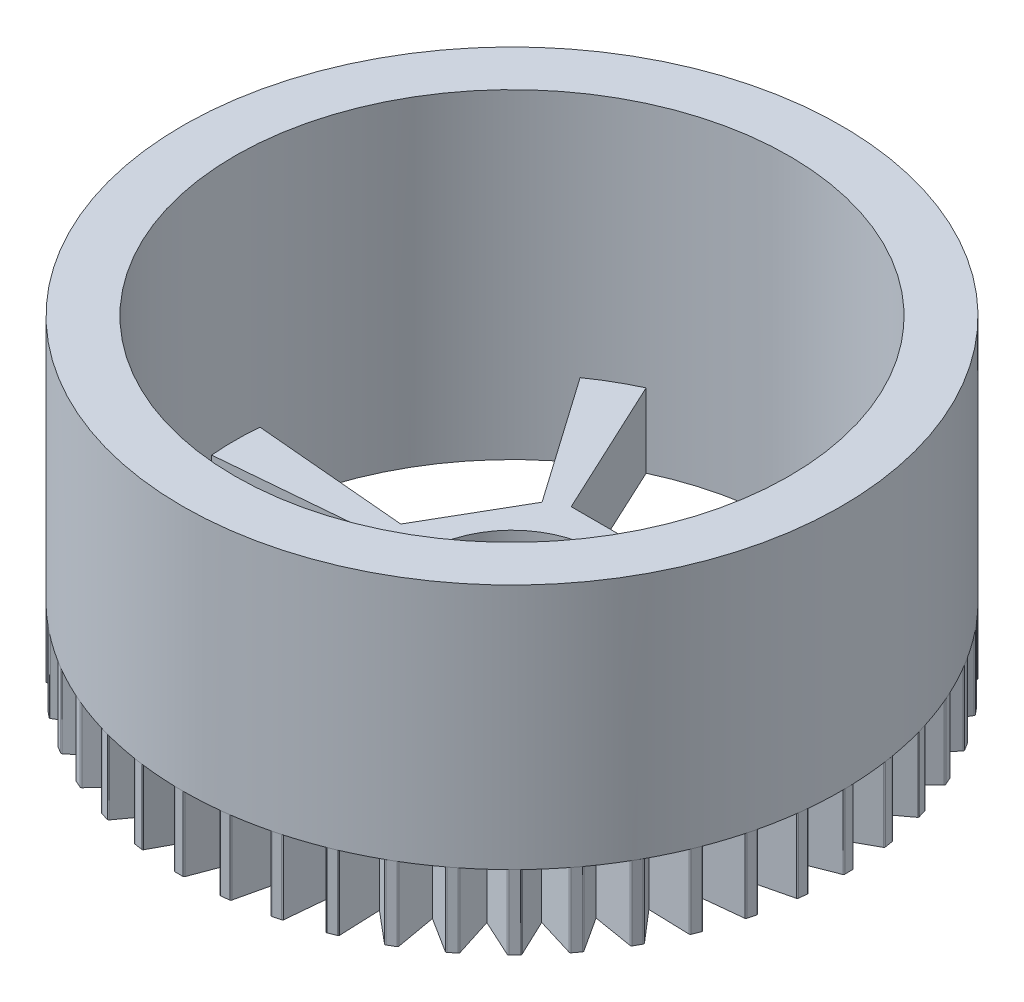
SolidWorks part; units mm, degrees
ref_plane "前视基准面" through (0, 0, 0) normal (0, 0, 1) x (1, 0, 0)
ref_plane "上视基准面" through (0, 0, 0) normal (0, 1, 0) x (1, 0, 0)
ref_plane "右视基准面" through (0, 0, 0) normal (1, 0, 0) x (0, 0, -1)
other "Configuration Table"
sketch "草图2" plane through (0, 0, 0) normal (0, 1, 0) x (1, 0, 0)
  line L0 (-2.5981, 4.5) -> (2.5981, 4.5)
  line L1 (0, 0) -> (2.5981, 4.5) construction
  line L2 (-2.5981, 4.5) -> (0, 0) construction
  line L3 (2.5981, 4.5) -> (5.1962, 0)
  line L4 (5.1962, 0) -> (2.5981, -4.5)
  line L5 (2.5981, -4.5) -> (-2.5981, -4.5)
  line L6 (-2.5981, -4.5) -> (-5.1962, 0)
  line L7 (-5.1962, 0) -> (-2.5981, 4.5)
  line L8 (2.5981, -4.5) -> (5.625, -9.7428) construction
  line L9 (2.8479, -4.0673) -> (6.4527, -9.2155)
  line L10 (2.0984, -4.5) -> (4.7545, -10.196)
  line L11 (-2.8479, -4.0673) -> (-6.4527, -9.2155)
  line L12 (-2.0984, -4.5) -> (-4.7545, -10.196)
  line L13 (-4.9463, 0.4327) -> (-11.2072, 0.9805)
  line L14 (-4.9463, -0.4327) -> (-11.2072, -0.9805)
  line L15 (-2.0984, 4.5) -> (-4.7545, 10.196)
  line L16 (-2.8479, 4.0673) -> (-6.4527, 9.2155)
  line L17 (2.8479, 4.0673) -> (6.4527, 9.2155)
  line L18 (2.0984, 4.5) -> (4.7545, 10.196)
  line L19 (4.9463, -0.4327) -> (11.2072, -0.9805)
  line L20 (4.9463, 0.4327) -> (11.2072, 0.9805)
  line L21 (5.1685, -10.5522) -> (6.4856, -11.6573)
  line L22 (6.5427, -11.6623) -> (6.8285, -11.4973)
  line L23 (6.5542, -9.7522) -> (6.8527, -11.4453)
  line L24 (3.716, -11.1469) -> (4.874, -12.4177)
  line L25 (4.9299, -12.4303) -> (5.2351, -12.3049)
  line L26 (5.1959, -10.5388) -> (5.2661, -12.2566)
  line L27 (2.1971, -11.5428) -> (3.1753, -12.9566)
  line L28 (3.2291, -12.9765) -> (3.5483, -12.8929)
  line L29 (3.7448, -11.1373) -> (3.5854, -12.8491)
  line L30 (0.639, -11.7326) -> (1.4201, -13.2642)
  line L31 (1.4707, -13.2911) -> (1.7982, -13.2508)
  line L32 (2.227, -11.537) -> (1.8408, -13.2124)
  line L33 (-0.9305, -11.7131) -> (-0.3606, -13.3351)
  line L34 (-0.3139, -13.3686) -> (0.016, -13.3722)
  line L35 (0.6694, -11.7309) -> (0.0634, -13.3399)
  line L36 (-2.4834, -11.4846) -> (-2.1347, -13.1681)
  line L37 (-2.093, -13.2074) -> (-1.7665, -13.2551)
  line L38 (-0.9002, -11.7155) -> (-1.7152, -13.2293)
  line L39 (-3.992, -11.0511) -> (-3.8708, -12.7661)
  line L40 (-3.8347, -12.8106) -> (-3.5174, -12.9013)
  line L41 (-2.4537, -11.491) -> (-3.4632, -12.8826)
  line L42 (-5.4294, -10.4204) -> (-5.5378, -12.1362)
  line L43 (-5.508, -12.1852) -> (-5.2056, -12.3174)
  line L44 (-3.9634, -11.0614) -> (-5.1494, -12.3061)
  line L45 (-6.7698, -9.6037) -> (-7.106, -11.2898)
  line L46 (-7.0829, -11.3423) -> (-6.8009, -11.5137)
  line L47 (-5.4024, -10.4344) -> (-6.7437, -11.5099)
  line L48 (-7.9895, -8.6157) -> (-8.5474, -10.242)
  line L49 (-8.5315, -10.2971) -> (-8.2749, -10.5044)
  line L50 (-6.7449, -9.6213) -> (-8.2176, -10.5084)
  line L51 (-9.0666, -7.474) -> (-9.8363, -9.0113)
  line L52 (-9.8279, -9.0681) -> (-9.6011, -9.3078)
  line L53 (-7.9671, -8.6364) -> (-9.5449, -9.3193)
  line L54 (-9.9818, -6.1988) -> (-10.9496, -7.6199)
  line L55 (-10.9488, -7.6772) -> (-10.7561, -7.945)
  line L56 (-9.0472, -7.4974) -> (-10.7019, -7.9639)
  line L57 (-10.719, -4.8131) -> (-11.8675, -6.0924)
  line L58 (-11.8744, -6.1494) -> (-11.7191, -6.4405)
  line L59 (-9.9657, -6.2247) -> (-11.6679, -6.4665)
  line L60 (-11.2649, -3.3414) -> (-12.5737, -4.4563)
  line L61 (-12.5881, -4.5118) -> (-12.4729, -4.821)
  line L62 (-10.7065, -4.8408) -> (-12.4257, -4.8536)
  line L63 (-11.6097, -1.8101) -> (-13.0554, -2.7406)
  line L64 (-13.0772, -2.7937) -> (-13.0042, -3.1155)
  line L65 (-11.2562, -3.3706) -> (-12.9618, -3.1541)
  line L66 (-11.7474, -0.2466) -> (-13.3043, -0.976)
  line L67 (-13.3328, -1.0258) -> (-13.3035, -1.3544)
  line L68 (-11.605, -1.8402) -> (-13.2665, -1.3983)
  line L69 (-11.6755, 1.3214) -> (-13.3156, 0.8059)
  line L70 (-13.3506, 0.7605) -> (-13.3653, 0.4308)
  line L71 (-11.7467, -0.277) -> (-13.3345, 0.3824)
  line L72 (-11.3952, 2.8658) -> (-13.0894, 2.5736)
  line L73 (-13.1301, 2.5331) -> (-13.1886, 2.2084)
  line L74 (-11.6788, 1.2912) -> (-13.1646, 2.1563)
  line L75 (-10.9115, 4.3591) -> (-12.6296, 4.2952)
  line L76 (-12.6753, 4.2606) -> (-12.7766, 3.9466)
  line L77 (-11.4025, 2.8363) -> (-12.7597, 3.8917)
  line L78 (-10.2331, 5.7745) -> (-11.9444, 5.9403)
  line L79 (-11.9943, 5.9121) -> (-12.1366, 5.6143)
  line L80 (-10.9228, 4.3308) -> (-12.1271, 5.5577)
  line L81 (-9.3722, 7.087) -> (-11.0461, 7.4793)
  line L82 (-11.0993, 7.458) -> (-11.28, 7.1819)
  line L83 (-10.2481, 5.748) -> (-11.2782, 7.1245)
  line L84 (-8.3439, 8.2729) -> (-9.9506, 8.8849)
  line L85 (-10.0062, 8.8708) -> (-10.2221, 8.6212)
  line L86 (-9.3905, 7.0627) -> (-10.2279, 8.5642)
  line L87 (-7.1668, 9.3112) -> (-8.6776, 10.1319)
  line L88 (-8.7346, 10.1254) -> (-8.9818, 9.9068)
  line L89 (-8.3654, 8.2513) -> (-8.9952, 9.851)
  line L90 (-5.8618, 10.1834) -> (-7.2497, 11.1981)
  line L91 (-7.3071, 11.1993) -> (-7.5812, 11.0156)
  line L92 (-7.1909, 9.2926) -> (-7.6019, 10.9621)
  line L93 (-4.4522, 10.8738) -> (-5.6925, 12.0645)
  line L94 (-5.7492, 12.0733) -> (-6.0453, 11.9277)
  line L95 (-5.8882, 10.1682) -> (-6.073, 11.8775)
  line L96 (-2.9631, 11.3702) -> (-4.0337, 12.7156)
  line L97 (-4.0887, 12.7318) -> (-4.4016, 12.6271)
  line L98 (-4.4804, 10.8623) -> (-4.4357, 12.581)
  line L99 (-1.4212, 11.6637) -> (-2.3028, 13.1397)
  line L100 (-2.3552, 13.1632) -> (-2.6793, 13.1011)
  line L101 (-2.9926, 11.3625) -> (-2.7192, 13.0599)
  line L102 (0.1461, 11.7491) -> (-0.5309, 13.3294)
  line L103 (-0.5797, 13.3597) -> (-0.9092, 13.3413)
  line L104 (-1.4514, 11.66) -> (-0.9542, 13.3058)
  line L105 (1.7108, 11.6248) -> (1.2504, 13.2813)
  line L106 (1.2062, 13.3177) -> (0.8772, 13.3434)
  line L107 (0.1157, 11.7494) -> (0.8278, 13.3143)
  line L108 (3.245, 11.293) -> (3.0095, 12.9961)
  line L109 (2.9705, 13.0381) -> (2.6479, 13.1075)
  line L110 (1.6807, 11.6292) -> (2.595, 13.0852)
  line L111 (4.7212, 10.7598) -> (4.7149, 12.479)
  line L112 (4.6818, 12.5259) -> (4.3713, 12.6376)
  line L113 (3.2157, 11.3014) -> (4.3159, 12.6225)
  line L114 (6.1133, 10.0345) -> (6.3361, 11.7392)
  line L115 (6.3095, 11.7901) -> (6.0167, 11.9422)
  line L116 (4.6933, 10.772) -> (5.9599, 11.9347)
  line L117 (7.3962, 9.1301) -> (7.8442, 10.79)
  line L118 (7.8247, 10.8439) -> (7.5548, 11.0337)
  line L119 (6.0872, 10.0503) -> (7.4974, 11.0338)
  line L120 (8.5471, 8.0628) -> (9.2124, 9.6482)
  line L121 (9.2003, 9.7042) -> (8.958, 9.9283)
  line L122 (7.3725, 9.1493) -> (8.9012, 9.936)
  line L123 (9.5455, 6.8517) -> (10.4162, 8.3342)
  line L124 (10.4116, 8.3914) -> (10.2014, 8.6457)
  line L125 (8.5262, 8.085) -> (10.1461, 8.661)
  line L126 (10.3736, 5.5183) -> (11.4341, 6.8715)
  line L127 (11.4372, 6.9288) -> (11.2627, 7.2089)
  line L128 (9.5277, 6.8764) -> (11.21, 7.2314)
  line L129 (11.0165, 4.0864) -> (12.2479, 5.2862)
  line L130 (12.2586, 5.3425) -> (12.1231, 5.6434)
  line L131 (10.3593, 5.5451) -> (12.0738, 5.6727)
  line L132 (11.4629, 2.5815) -> (12.8432, 3.6065)
  line L133 (12.8614, 3.6609) -> (12.7671, 3.9772)
  line L134 (11.0059, 4.1149) -> (12.7222, 4.0128)
  line L135 (11.7047, 1.0307) -> (13.2093, 1.8625)
  line L136 (13.2345, 1.914) -> (13.1833, 2.24)
  line L137 (11.4562, 2.6112) -> (13.1435, 2.2813)
  line L138 (11.7376, -0.5386) -> (13.3397, 0.0852)
  line L139 (13.3716, 0.1329) -> (13.3642, 0.4628)
  line L140 (11.702, 1.061) -> (13.3303, 0.5091)
  line L141 (11.5611, -2.0983) -> (13.2321, -1.6935)
  line L142 (13.27, -1.6505) -> (13.3067, -1.3226)
  line L143 (11.739, -0.5082) -> (13.2792, -1.2722)
  line L144 (11.1783, -3.6205) -> (12.8883, -3.4421)
  line L145 (12.9316, -3.4045) -> (13.0117, -3.0844)
  line L146 (11.5665, -2.0683) -> (12.9912, -3.0308)
  line L147 (10.596, -5.0781) -> (12.3145, -5.1292)
  line L148 (12.3624, -5.0977) -> (12.4845, -4.7911)
  line L149 (11.1876, -3.5916) -> (12.4713, -4.7353)
  line L150 (9.8246, -6.4451) -> (11.521, -6.7248)
  line L151 (11.5727, -6.7) -> (11.7345, -6.4124)
  line L152 (10.6091, -5.0507) -> (11.7288, -6.3553)
  line L153 (8.8779, -7.6971) -> (10.5218, -8.2004)
  line L154 (10.5764, -8.1827) -> (10.7751, -7.9192)
  line L155 (9.8413, -6.4197) -> (10.7771, -7.8619)
  line L156 (7.7727, -8.8118) -> (9.335, -9.5297)
  line L157 (9.3914, -9.5194) -> (9.6234, -9.2848)
  line L158 (8.8978, -7.6741) -> (9.6331, -9.2282)
  line L159 (6.5289, -9.7691) -> (7.9815, -10.6889)
  line L160 (8.0388, -10.6862) -> (8.3, -10.4846)
  line L161 (7.7955, -8.7916) -> (8.3171, -10.4298)
  circle A0 centre (0, 0) radius 3.5
  circle A1 centre (0, 0) radius 11.25
  circle A2 centre (0, 0) radius 11.75 construction
  arc A3 (6.8527, -11.4453) -> (6.8285, -11.4973) centre (6.8035, -11.454) cw
  arc A4 (6.4856, -11.6573) -> (6.5427, -11.6623) centre (6.5177, -11.619) ccw
  arc A5 (4.874, -12.4177) -> (4.9299, -12.4303) centre (4.9109, -12.3841) ccw
  arc A6 (5.2661, -12.2566) -> (5.2351, -12.3049) centre (5.2161, -12.2586) cw
  arc A7 (3.1753, -12.9566) -> (3.2291, -12.9765) centre (3.2165, -12.9281) ccw
  arc A8 (3.5854, -12.8491) -> (3.5483, -12.8929) centre (3.5357, -12.8445) cw
  arc A9 (1.4201, -13.2642) -> (1.4707, -13.2911) centre (1.4646, -13.2415) ccw
  arc A10 (1.8408, -13.2124) -> (1.7982, -13.2508) centre (1.7921, -13.2012) cw
  arc A11 (-0.3606, -13.3351) -> (-0.3139, -13.3686) centre (-0.3134, -13.3186) ccw
  arc A12 (0.0634, -13.3399) -> (0.016, -13.3722) centre (0.0166, -13.3222) cw
  arc A13 (-2.1347, -13.1681) -> (-2.093, -13.2074) centre (-2.0858, -13.158) ccw
  arc A14 (-1.7152, -13.2293) -> (-1.7665, -13.2551) centre (-1.7592, -13.2056) cw
  arc A15 (-3.8708, -12.7661) -> (-3.8347, -12.8106) centre (-3.8209, -12.7625) ccw
  arc A16 (-3.4632, -12.8826) -> (-3.5174, -12.9013) centre (-3.5037, -12.8533) cw
  arc A17 (-5.5378, -12.1362) -> (-5.508, -12.1852) centre (-5.4879, -12.1394) ccw
  arc A18 (-5.1494, -12.3061) -> (-5.2056, -12.3174) centre (-5.1856, -12.2716) cw
  arc A19 (-7.106, -11.2898) -> (-7.0829, -11.3423) centre (-7.057, -11.2996) ccw
  arc A20 (-6.7437, -11.5099) -> (-6.8009, -11.5137) centre (-6.775, -11.4709) cw
  arc A21 (-8.5474, -10.242) -> (-8.5315, -10.2971) centre (-8.5001, -10.2582) ccw
  arc A22 (-8.2176, -10.5084) -> (-8.2749, -10.5044) centre (-8.2434, -10.4656) cw
  arc A23 (-9.8363, -9.0113) -> (-9.8279, -9.0681) centre (-9.7916, -9.0337) ccw
  arc A24 (-9.5449, -9.3193) -> (-9.6011, -9.3078) centre (-9.5648, -9.2734) cw
  arc A25 (-10.9496, -7.6199) -> (-10.9488, -7.6772) centre (-10.9083, -7.648) ccw
  arc A26 (-10.7019, -7.9639) -> (-10.7561, -7.945) centre (-10.7155, -7.9158) cw
  arc A27 (-11.8675, -6.0924) -> (-11.8744, -6.1494) centre (-11.8303, -6.1258) ccw
  arc A28 (-11.6679, -6.4665) -> (-11.7191, -6.4405) centre (-11.675, -6.417) cw
  arc A29 (-12.5737, -4.4563) -> (-12.5881, -4.5118) centre (-12.5412, -4.4944) ccw
  arc A30 (-12.4257, -4.8536) -> (-12.4729, -4.821) centre (-12.4261, -4.8036) cw
  arc A31 (-13.0554, -2.7406) -> (-13.0772, -2.7937) centre (-13.0284, -2.7827) ccw
  arc A32 (-12.9618, -3.1541) -> (-13.0042, -3.1155) centre (-12.9555, -3.1045) cw
  arc A33 (-13.3043, -0.976) -> (-13.3328, -1.0258) centre (-13.283, -1.0213) ccw
  arc A34 (-13.2665, -1.3983) -> (-13.3035, -1.3544) centre (-13.2537, -1.35) cw
  arc A35 (-13.3156, 0.8059) -> (-13.3506, 0.7605) centre (-13.3006, 0.7582) ccw
  arc A36 (-13.3345, 0.3824) -> (-13.3653, 0.4308) centre (-13.3153, 0.4286) cw
  arc A37 (-13.0894, 2.5736) -> (-13.1301, 2.5331) centre (-13.0809, 2.5243) ccw
  arc A38 (-13.1646, 2.1563) -> (-13.1886, 2.2084) centre (-13.1394, 2.1995) cw
  arc A39 (-12.6296, 4.2952) -> (-12.6753, 4.2606) centre (-12.6277, 4.2453) ccw
  arc A40 (-12.7597, 3.8917) -> (-12.7766, 3.9466) centre (-12.729, 3.9312) cw
  arc A41 (-11.9444, 5.9403) -> (-11.9943, 5.9121) centre (-11.9492, 5.8905) ccw
  arc A42 (-12.1271, 5.5577) -> (-12.1366, 5.6143) centre (-12.0915, 5.5928) cw
  arc A43 (-11.0461, 7.4793) -> (-11.0993, 7.458) centre (-11.0575, 7.4306) ccw
  arc A44 (-11.2782, 7.1245) -> (-11.28, 7.1819) centre (-11.2381, 7.1545) cw
  arc A45 (-9.9506, 8.8849) -> (-10.0062, 8.8708) centre (-9.9684, 8.8381) ccw
  arc A46 (-10.2279, 8.5642) -> (-10.2221, 8.6212) centre (-10.1843, 8.5885) cw
  arc A47 (-8.6776, 10.1319) -> (-8.7346, 10.1254) centre (-8.7015, 10.0879) ccw
  arc A48 (-8.9952, 9.851) -> (-8.9818, 9.9068) centre (-8.9486, 9.8693) cw
  arc A49 (-7.2497, 11.1981) -> (-7.3071, 11.1993) centre (-7.2792, 11.1577) ccw
  arc A50 (-7.6019, 10.9621) -> (-7.5812, 11.0156) centre (-7.5533, 10.974) cw
  arc A51 (-5.6925, 12.0645) -> (-5.7492, 12.0733) centre (-5.7271, 12.0284) ccw
  arc A52 (-6.073, 11.8775) -> (-6.0453, 11.9277) centre (-6.0233, 11.8829) cw
  arc A53 (-4.0337, 12.7156) -> (-4.0887, 12.7318) centre (-4.0728, 12.6844) ccw
  arc A54 (-4.4357, 12.581) -> (-4.4016, 12.6271) centre (-4.3857, 12.5797) cw
  arc A55 (-2.3028, 13.1397) -> (-2.3552, 13.1632) centre (-2.3458, 13.1141) ccw
  arc A56 (-2.7192, 13.0599) -> (-2.6793, 13.1011) centre (-2.6698, 13.052) cw
  arc A57 (-0.5309, 13.3294) -> (-0.5797, 13.3597) centre (-0.5769, 13.3097) ccw
  arc A58 (-0.9542, 13.3058) -> (-0.9092, 13.3413) centre (-0.9064, 13.2914) cw
  arc A59 (1.2504, 13.2813) -> (1.2062, 13.3177) centre (1.2023, 13.2679) ccw
  arc A60 (0.8278, 13.3143) -> (0.8772, 13.3434) centre (0.8733, 13.2936) cw
  arc A61 (3.0095, 12.9961) -> (2.9705, 13.0381) centre (2.96, 12.9893) ccw
  arc A62 (2.595, 13.0852) -> (2.6479, 13.1075) centre (2.6374, 13.0586) cw
  arc A63 (4.7149, 12.479) -> (4.6818, 12.5259) centre (4.6649, 12.4788) ccw
  arc A64 (4.3159, 12.6225) -> (4.3713, 12.6376) centre (4.3544, 12.5905) cw
  arc A65 (6.3361, 11.7392) -> (6.3095, 11.7901) centre (6.2865, 11.7457) ccw
  arc A66 (5.9599, 11.9347) -> (6.0167, 11.9422) centre (5.9937, 11.8978) cw
  arc A67 (7.8442, 10.79) -> (7.8247, 10.8439) centre (7.796, 10.803) ccw
  arc A68 (7.4974, 11.0338) -> (7.5548, 11.0337) centre (7.526, 10.9928) cw
  arc A69 (9.2124, 9.6482) -> (9.2003, 9.7042) centre (9.1663, 9.6675) ccw
  arc A70 (8.9012, 9.936) -> (8.958, 9.9283) centre (8.9241, 9.8916) cw
  arc A71 (10.4162, 8.3342) -> (10.4116, 8.3914) centre (10.3731, 8.3595) ccw
  arc A72 (10.1461, 8.661) -> (10.2014, 8.6457) centre (10.1628, 8.6139) cw
  arc A73 (11.4341, 6.8715) -> (11.4372, 6.9288) centre (11.3947, 6.9023) ccw
  arc A74 (11.21, 7.2314) -> (11.2627, 7.2089) centre (11.2203, 7.1824) cw
  arc A75 (12.2479, 5.2862) -> (12.2586, 5.3425) centre (12.2131, 5.322) ccw
  arc A76 (12.0738, 5.6727) -> (12.1231, 5.6434) centre (12.0775, 5.6228) cw
  arc A77 (12.8432, 3.6065) -> (12.8614, 3.6609) centre (12.8134, 3.6467) ccw
  arc A78 (12.7222, 4.0128) -> (12.7671, 3.9772) centre (12.7192, 3.9629) cw
  arc A79 (13.2093, 1.8625) -> (13.2345, 1.914) centre (13.1852, 1.9063) ccw
  arc A80 (13.1435, 2.2813) -> (13.1833, 2.24) centre (13.1339, 2.2322) cw
  arc A81 (13.3397, 0.0852) -> (13.3716, 0.1329) centre (13.3216, 0.1318) ccw
  arc A82 (13.3303, 0.5091) -> (13.3642, 0.4628) centre (13.3142, 0.4617) cw
  arc A83 (13.2321, -1.6935) -> (13.27, -1.6505) centre (13.2203, -1.6449) ccw
  arc A84 (13.2792, -1.2722) -> (13.3067, -1.3226) centre (13.257, -1.317) cw
  arc A85 (12.8883, -3.4421) -> (12.9316, -3.4045) centre (12.8831, -3.3924) ccw
  arc A86 (12.9912, -3.0308) -> (13.0117, -3.0844) centre (12.9632, -3.0722) cw
  arc A87 (12.3145, -5.1292) -> (12.3624, -5.0977) centre (12.316, -5.0792) ccw
  arc A88 (12.4713, -4.7353) -> (12.4845, -4.7911) centre (12.438, -4.7726) cw
  arc A89 (11.521, -6.7248) -> (11.5727, -6.7) centre (11.5291, -6.6755) ccw
  arc A90 (11.7288, -6.3553) -> (11.7345, -6.4124) centre (11.6909, -6.3879) cw
  arc A91 (10.5218, -8.2004) -> (10.5764, -8.1827) centre (10.5365, -8.1526) ccw
  arc A92 (10.7771, -7.8619) -> (10.7751, -7.9192) centre (10.7352, -7.8891) cw
  arc A93 (9.335, -9.5297) -> (9.3914, -9.5194) centre (9.3558, -9.4842) ccw
  arc A94 (9.6331, -9.2282) -> (9.6234, -9.2848) centre (9.5879, -9.2496) cw
  arc A95 (7.9815, -10.6889) -> (8.0388, -10.6862) centre (8.0082, -10.6466) ccw
  arc A96 (8.3171, -10.4298) -> (8.3, -10.4846) centre (8.2695, -10.445) cw
  point P6 (0, 4.5)
  point P18 (6.6856, -11.5798)
  point P47 (6.8588, -11.4798)
  point P50 (6.5124, -11.6798)
  dimension "D1" = 7
  dimension "D5" = 22.5
  dimension "D8" = 23.5
  dimension "D2" = 110
  dimension "D11" = 0.05
  dimension "D3" = 4.5
  dimension "D6" = 5
  dimension "D9" = 0.2
  dimension "D10" = 0.8
  dimension "D4" = 6
  dimension "D7" = 6
  dimension "D12" = 47
extrude "凸台-拉伸4" add sketch "草图2" along normal blind 3
sketch "草图4" plane through (0, 3, 0) normal (0, 1, 0) x (1, 0, 0)
  line L0 (12.3624, -5.0977) -> (12.4845, -4.7911) construction
  circle A0 centre (0, 0) radius 13.3712
  circle A1 centre (0, 0) radius 13.3712
  circle A3 centre (0, 0) radius 11.25
  arc A4 (6.4527, -9.2155) -> (11.2072, -0.9805) centre (0, 0) ccw construction
extrude "凸台-拉伸5" add sketch "草图4" along normal blind 10 contours A0 A3
